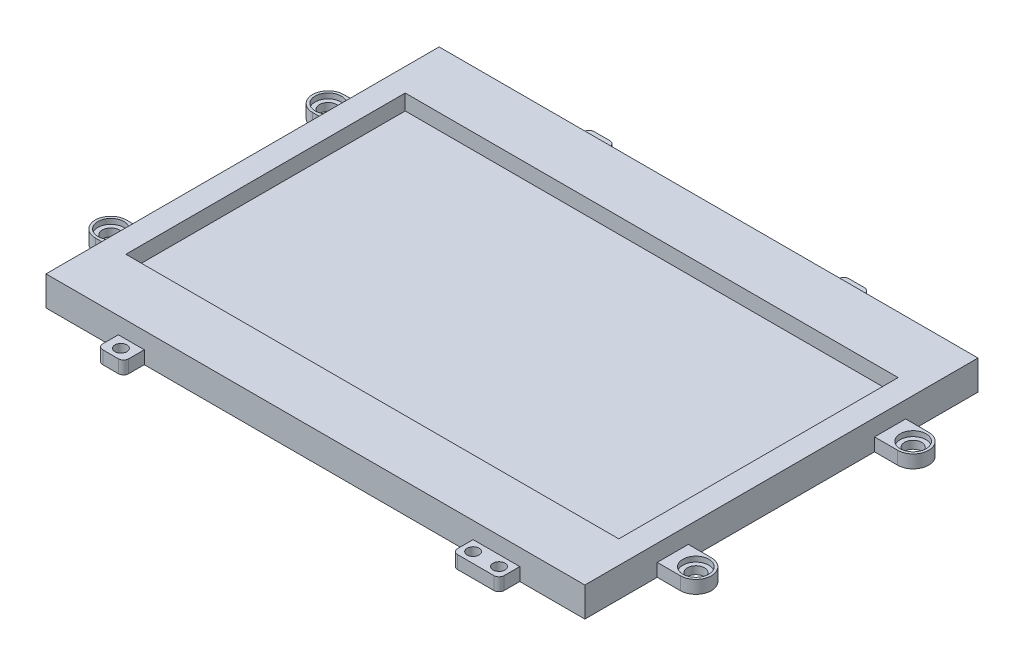
SolidWorks part; units mm, degrees
ref_plane "前视基准面" through (0, 0, 0) normal (0, 0, 1) x (1, 0, 0)
ref_plane "上视基准面" through (0, 0, 0) normal (0, 1, 0) x (1, 0, 0)
ref_plane "右视基准面" through (0, 0, 0) normal (1, 0, 0) x (0, 0, -1)
sketch "草图1" plane through (0, 0, 0) normal (0, 1, 0) x (1, 0, 0)
  line L1 (-51.95, 37.9) -> (51.95, 37.9)
  line L2 (-51.95, 37.9) -> (-51.95, -37.9)
  line L3 (-51.95, -37.9) -> (51.95, -37.9)
  line L4 (51.95, 37.9) -> (51.95, -37.9)
  line L5 (-51.95, 37.9) -> (51.95, -37.9) construction
  line L6 (-51.95, -37.9) -> (51.95, 37.9) construction
  point P0 (0, 0)
  dimension "D1" = 103.9
  dimension "D2" = 75.8
extrude "凸台-拉伸1" add sketch "草图1" along normal blind 5.7
sketch "草图2" plane through (0, 0, 0) normal (0, 1, 0) x (1, 0, 0)
  line L0 (0, 55.8696) -> (0, -47.6866) construction
  line L1 (74.1289, 0) -> (-61.5401, 0) construction
  line L2 (51.95, 37.9) -> (-51.95, 37.9) construction
  line L3 (27.05, 37.9) -> (22.05, 37.9)
  line L4 (-27.05, 41.9) -> (-22.05, 41.9)
  line L5 (-27.05, 41.9) -> (-27.05, 37.9)
  line L6 (-27.05, 37.9) -> (-22.05, 37.9)
  line L7 (-22.05, 41.9) -> (-22.05, 37.9)
  line L8 (-27.05, 41.9) -> (-22.05, 37.9) construction
  line L9 (-27.05, 37.9) -> (-22.05, 41.9) construction
  line L10 (27.05, 41.9) -> (27.05, 37.9)
  line L11 (27.05, 41.9) -> (22.05, 41.9)
  line L12 (22.05, 41.9) -> (22.05, 37.9)
  line L13 (-56.4, -23.95) -> (-51.95, -23.95)
  line L14 (-51.95, 37.9) -> (-51.95, -37.9) construction
  line L15 (-56.4, -17.95) -> (-51.95, -17.95)
  line L17 (56.4, -17.95) -> (51.95, -17.95)
  line L18 (56.4, -23.95) -> (51.95, -23.95)
  line L19 (56.4, 17.95) -> (51.95, 17.95)
  line L20 (56.4, 23.95) -> (51.95, 23.95)
  line L21 (-56.4, 17.95) -> (-51.95, 17.95)
  line L22 (-56.4, 23.95) -> (-51.95, 23.95)
  line L23 (-51.95, -37.9) -> (51.95, -37.9) construction
  line L24 (-51.95, 17.95) -> (-51.95, 23.95)
  line L25 (-38, -41.9) -> (-33, -41.9)
  line L26 (-38, -41.9) -> (-38, -37.9)
  line L27 (-38, -37.9) -> (-33, -37.9)
  line L28 (-33, -41.9) -> (-33, -37.9)
  line L29 (-38, -41.9) -> (-33, -37.9) construction
  line L30 (-38, -37.9) -> (-33, -41.9) construction
  line L31 (-51.95, -23.95) -> (-51.95, -17.95)
  line L32 (30.4, -41.9) -> (39.4, -41.9)
  line L33 (30.4, -41.9) -> (30.4, -37.9)
  line L34 (30.4, -37.9) -> (39.4, -37.9)
  line L35 (39.4, -41.9) -> (39.4, -37.9)
  line L36 (30.4, -41.9) -> (39.4, -37.9) construction
  line L37 (30.4, -37.9) -> (39.4, -41.9) construction
  line L38 (51.95, -17.95) -> (51.95, -23.95)
  line L39 (51.95, 23.95) -> (51.95, 17.95)
  circle A0 centre (-56.4, 20.95) radius 1.65
  circle A1 centre (56.4, 20.95) radius 1.65
  circle A2 centre (-24.55, 39.9) radius 1.15
  circle A3 centre (24.55, 39.9) radius 1.15
  circle A4 centre (-56.4, -20.95) radius 1.65
  circle A5 centre (56.4, -20.95) radius 1.65
  circle A6 centre (56.4, -20.95) radius 3
  circle A7 centre (-56.4, -20.95) radius 3
  circle A8 centre (56.4, 20.95) radius 3
  circle A9 centre (-56.4, 20.95) radius 3
  circle A10 centre (-35.5, -39.9) radius 1.15
  circle A11 centre (32.4, -39.9) radius 1.15
  circle A12 centre (37.4, -39.9) radius 1.15
  point P63 (34.9, -39.9)
  dimension "D1" = 3.3
  dimension "D2" = 112.8
  dimension "D3" = 2.3
  dimension "D6" = 41.9
  dimension "D8" = 2.3
  dimension "D9" = 6
  dimension "D10" = 16.45
  dimension "D13" = 2.3
  dimension "D14" = 2.3
  dimension "D4" = 49.1
  dimension "D5" = 2
  dimension "D7" = 5
  dimension "D11" = 2
  dimension "D12" = 5
  dimension "D15" = 5
  dimension "D16" = 67.9
  dimension "D17" = 2
  dimension "D18" = 2
  dimension "D19" = 2.5
  dimension "D20" = 2
  dimension "D21" = 9
extrude "凸台-拉伸2" add sketch "草图2" along normal blind 2.5 contours L22 A9 L21 L24 | A9 A0 | L7 L4 L5 L6 A2 | L11 L12 L3 L10 A3 | A8 L20 L39 L19 | A8 A1 | A6 A5 | L18 A6 L17 L38 | L32 L35 L34 L33 A12 A11 | L25 L28 L27 L26 A10 | A7 A4 | A7 L13 L31 L15
fillet "圆角1" radius 1 8 edges at (-27.05, 1.25, -41.9) (-22.05, 1.25, -41.9) (22.05, 1.25, -41.9) (27.05, 1.25, -41.9) (30.4, 1.25, 41.9) (39.4, 1.25, 41.9) (-38, 1.25, 41.9) (-33, 1.25, 41.9)
sketch "草图3" plane through (0, 2.5, 0) normal (0, 1, 0) x (1, 0, 0)
  circle A0 centre (-56.4, -20.95) radius 2.5
  circle A1 centre (-56.4, 20.95) radius 2.5
  circle A2 centre (56.4, 20.95) radius 2.5
  circle A3 centre (56.4, -20.95) radius 2.5
  dimension "D1" = 5
  dimension "D2" = 5
  dimension "D3" = 5
  dimension "D4" = 5
extrude "切除-拉伸1" cut sketch "草图3" against normal blind 1
sketch "草图4" plane through (0, 5.7, 0) normal (0, 1, 0) x (1, 0, 0)
  line L0 (-63.748, 0) -> (76.5332, 0) construction
  line L1 (0, 43.7417) -> (0, -46.3461) construction
  line L3 (-47.52, 26.93) -> (47.52, 26.93)
  line L4 (-47.52, 26.93) -> (-47.52, -26.93)
  line L5 (-47.52, -26.93) -> (47.52, -26.93)
  line L6 (47.52, 26.93) -> (47.52, -26.93)
  line L7 (-47.52, 26.93) -> (47.52, -26.93) construction
  line L8 (-47.52, -26.93) -> (47.52, 26.93) construction
  point P5 (0, 0)
  dimension "D1" = 95.04
  dimension "D2" = 53.86
extrude "切除-拉伸2" cut sketch "草图4" against normal blind 3
